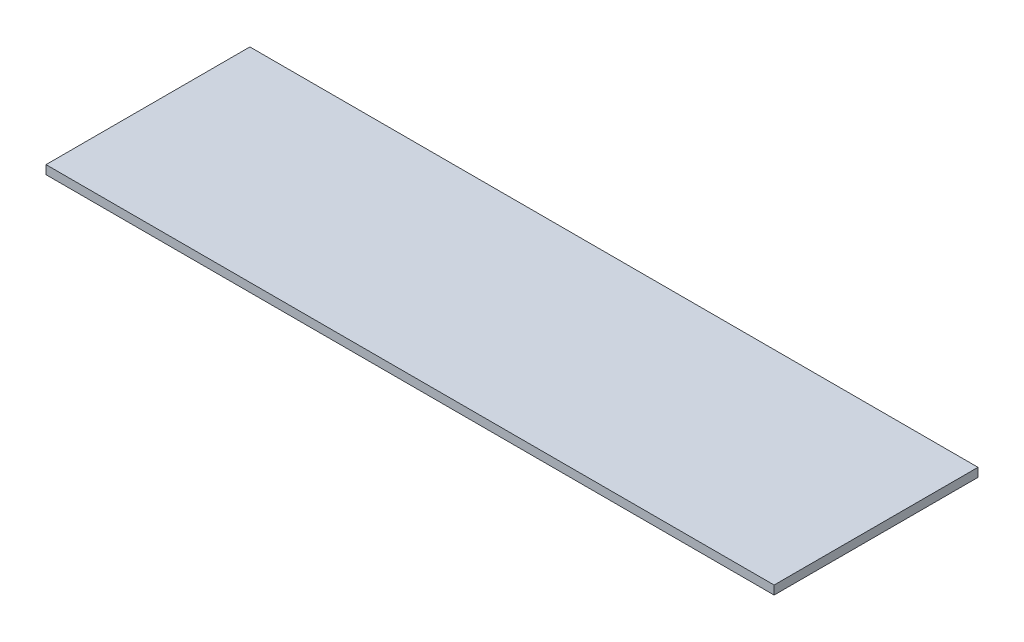
SolidWorks part; units mm, degrees
ref_plane "Front Plane" through (0, 0, 0) normal (0, 0, 1) x (1, 0, 0)
ref_plane "Top Plane" through (0, 0, 0) normal (0, 1, 0) x (1, 0, 0)
ref_plane "Right Plane" through (0, 0, 0) normal (1, 0, 0) x (0, 0, -1)
sketch "Sketch1" plane through (0, 0, 0) normal (0, 1, 0) x (1, 0, 0)
  line L1 (-125, -35) -> (125, -35)
  line L2 (-125, -35) -> (-125, 35)
  line L3 (-125, 35) -> (125, 35)
  line L4 (125, -35) -> (125, 35)
  line L5 (-125, -35) -> (125, 35) construction
  line L6 (-125, 35) -> (125, -35) construction
  point P0 (0, 0)
  dimension "D1" = 250
  dimension "D2" = 70
extrude "Boss-Extrude1" add sketch "Sketch1" along normal blind 3
